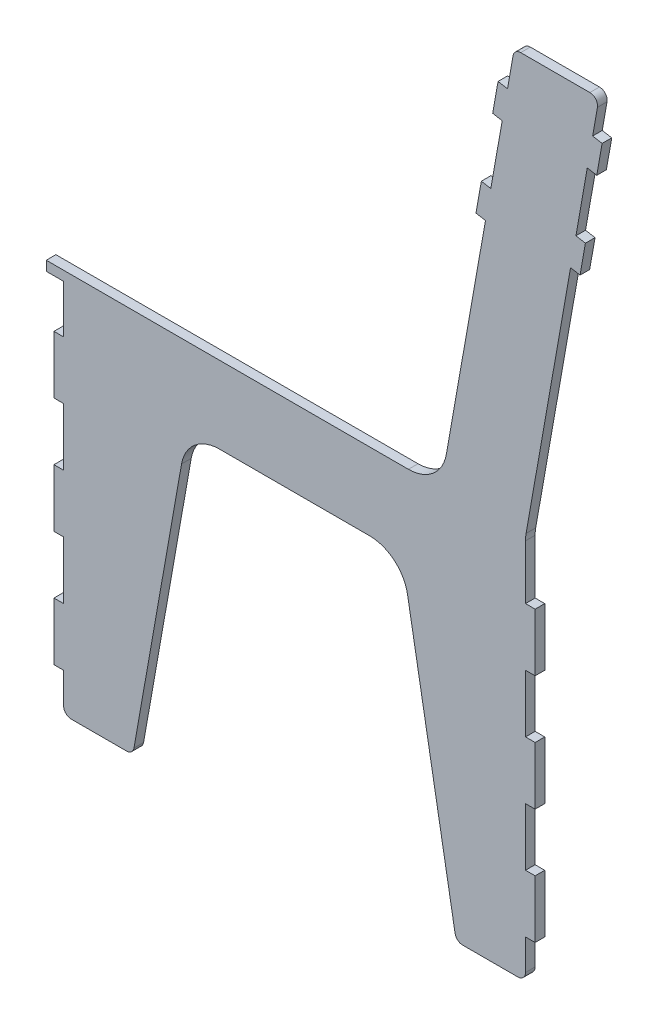
SolidWorks part; units mm, degrees
material "Beech"
ref_plane "Front" through (0, 0, 0) normal (0, 0, 1) x (1, 0, 0)
ref_plane "Top" through (0, 0, 0) normal (0, 1, 0) x (1, 0, 0)
ref_plane "Right" through (0, 0, 0) normal (1, 0, 0) x (0, 0, -1)
sketch "Sketch1" plane through (0, 0, 0) normal (0, 0, 1) x (1, 0, 0)
  line L0 (-50, 0) -> (50, 0) construction
  line L1 (-50, 0) -> (-50, -90) construction
  line L2 (50, 0) -> (50, -90) construction
  line L3 (-27.8938, -10) -> (-42, -90)
  line L4 (-27.8938, -10) -> (27.8938, -10)
  line L5 (27.8938, -10) -> (42, -90)
  line L6 (-60, 10) -> (-60, -90) construction
  line L7 (-60, 10) -> (60, 10) construction
  line L8 (60, 10) -> (60, -90) construction
  line L9 (62.5, 12.5) -> (62.5, -90) construction
  line L10 (-62.5, 12.5) -> (62.5, 12.5) construction
  line L11 (-62.5, 12.5) -> (-62.5, -90) construction
  line L12 (50.9912, 83.8606) -> (53.9432, 100.6023)
  line L13 (49.602, 75.9821) -> (37.9676, 10)
  line L14 (-60, 10) -> (-60, -90) construction
  line L15 (-62.5, 12.5) -> (-62.5, -90) construction
  line L16 (60, 10) -> (60, -90) construction
  line L17 (62.5, 12.5) -> (62.5, -90) construction
  line L18 (42, -90) -> (60, -90) construction
  line L19 (0, -5) -> (0, 7.3184) construction
  line L20 (60, -50) -> (60, -65)
  line L21 (62.5, -50) -> (60, -50)
  line L22 (62.5, -35) -> (62.5, -50)
  line L23 (60, -35) -> (62.5, -35)
  line L24 (60, -20) -> (60, -35)
  line L25 (62.5, -20) -> (60, -20)
  line L26 (62.5, -5) -> (62.5, -20)
  line L27 (60, -5) -> (62.5, -5)
  line L28 (60, 10) -> (60, -5)
  line L29 (-60, -90) -> (-42, -90)
  line L30 (42, -90) -> (60, -90)
  line L31 (60, -80) -> (60, -90)
  line L32 (60, 10) -> (79.1013, 118.3289) construction
  line L33 (79.1013, 118.3289) -> (57.0689, 118.3289)
  line L34 (57.0689, 118.3289) -> (37.9676, 10) construction
  line L35 (54.5303, 118.3289) -> (35.5056, 10.4341) construction
  line L36 (54.6069, 118.763) -> (35.5056, 10.4341) construction
  line L37 (57.0689, 118.3289) -> (55.3324, 108.4808)
  line L38 (55.3324, 108.4808) -> (52.8704, 108.9149)
  line L39 (52.8704, 108.9149) -> (51.4812, 101.0364)
  line L40 (51.4812, 101.0364) -> (53.9432, 100.6023)
  line L41 (-60, -35) -> (-62.5, -35)
  line L42 (49.602, 75.9821) -> (47.14, 76.4162)
  line L43 (47.14, 76.4162) -> (48.5292, 84.2947)
  line L44 (48.5292, 84.2947) -> (50.9912, 83.8606)
  line L45 (-62.5, -35) -> (-62.5, -50)
  line L46 (37.9676, 10) -> (-60, 10) construction
  line L47 (-60, 10) -> (-60, -5) construction
  line L48 (-60, -5) -> (-62.5, -5)
  line L49 (-62.5, -5) -> (-62.5, -20)
  line L50 (-62.5, -20) -> (-60, -20)
  line L51 (-60, -20) -> (-60, -35)
  line L52 (-62.5, -50) -> (-60, -50)
  line L53 (-60, -50) -> (-60, -65)
  line L54 (-60, -65) -> (-62.5, -65)
  line L55 (-62.5, -65) -> (-62.5, -80)
  line L56 (-62.5, -80) -> (-60, -80)
  line L57 (-60, -80) -> (-60, -90)
  line L58 (62.5, -65) -> (62.5, -80)
  line L59 (62.5, -80) -> (60, -80)
  line L60 (60, -65) -> (62.5, -65)
  line L61 (-60, -90) -> (-42, -90) construction
  line L62 (37.9676, 10) -> (-60, 10)
  line L66 (-60, 7.5) -> (-60, -5)
  line L67 (-60, 10) -> (-64.5, 10)
  line L68 (-64.5, 10) -> (-64.5, 7.5)
  line L69 (-64.5, 7.5) -> (-60, 7.5)
  line L71 (76.0522, 101.0364) -> (78.5142, 100.6023)
  line L72 (76.0522, 101.0364) -> (77.4414, 108.9149) construction
  line L73 (77.4414, 108.9149) -> (79.9034, 108.4808)
  line L74 (78.5142, 100.6023) -> (79.9034, 108.4808)
  line L75 (76.0522, 101.0364) -> (79.9034, 108.4808) construction
  line L76 (77.4414, 108.9149) -> (78.5142, 100.6023) construction
  line L80 (71.711, 76.4162) -> (74.173, 75.9821)
  line L81 (71.711, 76.4162) -> (73.1002, 84.2947) construction
  line L82 (74.173, 75.9821) -> (75.5622, 83.8606)
  line L83 (73.1002, 84.2947) -> (75.5622, 83.8606)
  line L84 (71.711, 76.4162) -> (75.5622, 83.8606) construction
  line L85 (74.173, 75.9821) -> (73.1002, 84.2947) construction
  line L86 (79.1013, 118.3289) -> (77.4414, 108.9149)
  line L87 (76.0522, 101.0364) -> (73.1002, 84.2947)
  line L88 (60, 10) -> (71.711, 76.4162)
  point P4 (0, 0)
  point P54 (77.9778, 104.7586)
  point P71 (73.6366, 80.1384)
  point P72 (52.1758, 104.9757)
  point P73 (72.4056, 80.3555)
  point P74 (47.8346, 80.3555)
  point P76 (76.7468, 104.9757)
  dimension "D1" = 90
  dimension "D2" = 2.5
  dimension "D3" = 100
  dimension "D4" = 90
  dimension "D5" = 10
  dimension "D8" = 2.5
  dimension "D10" = 170
  dimension "D11" = 110
  dimension "D14" = 100
  dimension "D15" = 100
  dimension "D16" = 18
  dimension "D17" = 8
  dimension "D18" = 10
  dimension "D19" = 17
  dimension "D13" = 15
  dimension "D6" = 10
  dimension "D7" = 4.5
  dimension "D12" = 2.5
extrude "Boss-Extrude1" add sketch "Sketch1" along normal blind 2.5
fillet "Fillet1" radius 2 6 edges at (57.0689, 118.3289, 1.25) (60, -90, 1.25) (42, -90, 1.25) (-60, -90, 1.25) (-42, -90, 1.25) (79.1013, 118.3289, 1.25)
fillet "Fillet2" radius 10 4 edges at (-27.8938, -10, 1.25) (27.8938, -10, 1.25) (37.9676, 10, 1.25) (60, 10, 1.25)
